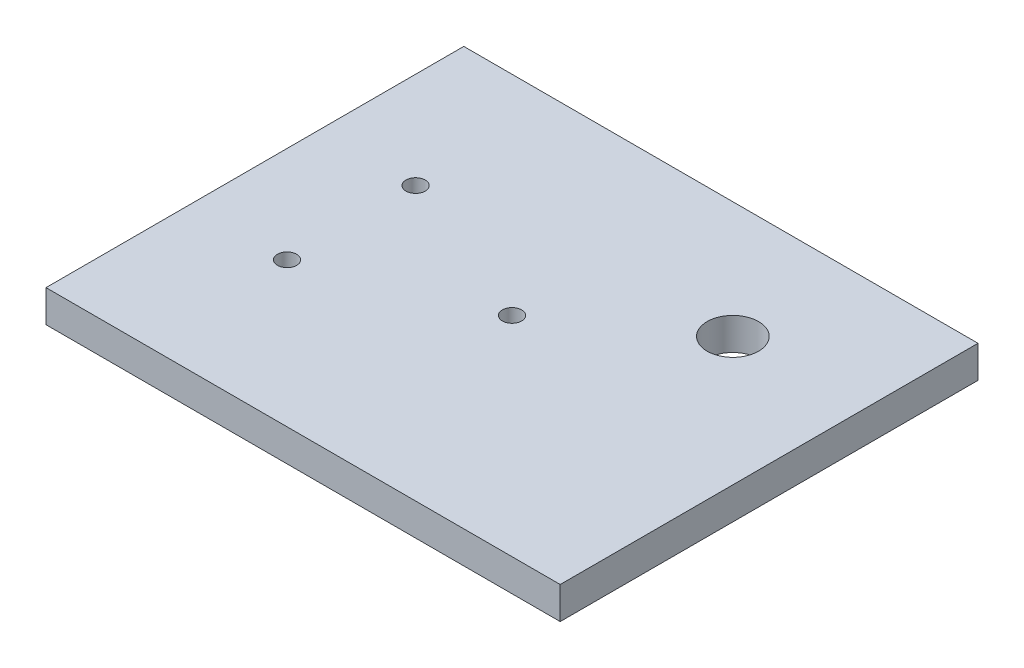
SolidWorks part; units mm, degrees
ref_plane "Front Plane" through (0, 0, 0) normal (0, 0, 1) x (1, 0, 0)
ref_plane "Top Plane" through (0, 0, 0) normal (0, 1, 0) x (1, 0, 0)
ref_plane "Right Plane" through (0, 0, 0) normal (1, 0, 0) x (0, 0, -1)
sketch "Sketch1" plane through (0, 0, 0) normal (0, 1, 0) x (1, 0, 0)
  line L0 (41.3967, -0.1161) -> (-38.6033, -0.1161) construction
  line L1 (-38.6033, -32.6161) -> (41.3967, -32.6161)
  line L2 (-38.6033, -32.6161) -> (-38.6033, 32.3839)
  line L3 (-38.6033, 32.3839) -> (41.3967, 32.3839)
  line L4 (41.3967, -32.6161) -> (41.3967, 32.3839)
  line L5 (-38.6033, -32.6161) -> (41.3967, 32.3839) construction
  line L6 (-38.6033, 32.3839) -> (41.3967, -32.6161) construction
  circle A0 centre (21.3967, 14.2449) radius 4
  circle A2 centre (-23.6033, 9.8839) radius 1.5
  circle A3 centre (-23.6033, -10.1161) radius 1.5
  circle A4 centre (1.3967, -0.1161) radius 1.5
  point P0 (1.3967, -0.1161)
  dimension "D3" = 8
  dimension "D4" = 3
  dimension "D6" = 15
  dimension "D7" = 20
  dimension "D8" = 3
  dimension "D1" = 80
  dimension "D2" = 65
  dimension "D5" = 22.5
extrude "Boss-Extrude1" add sketch "Sketch1" along normal blind 5
